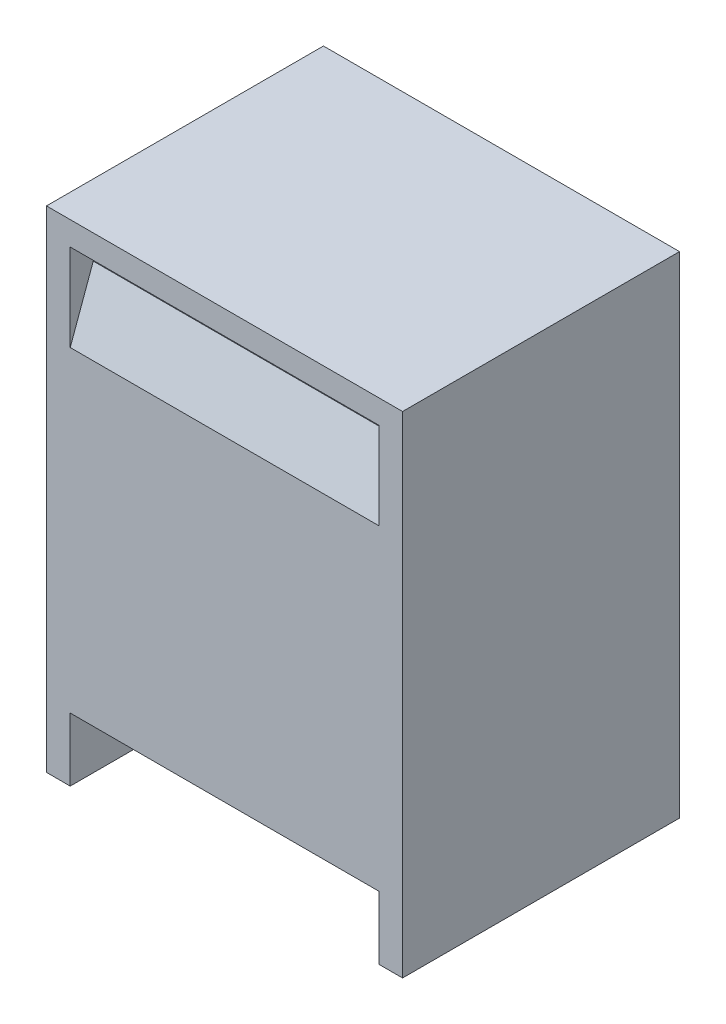
SolidWorks part; units mm, degrees
ref_plane "Alzado" through (0, 0, 0) normal (0, 0, 1) x (1, 0, 0)
ref_plane "Planta" through (0, 0, 0) normal (0, 1, 0) x (1, 0, 0)
ref_plane "Vista lateral" through (0, 0, 0) normal (1, 0, 0) x (0, 0, -1)
sketch "Croquis1" plane through (0, 0, 0) normal (0, 0, 1) x (1, 0, 0)
  line L1 (0, 0) -> (450, 0)
  line L2 (0, 0) -> (0, 620)
  line L3 (0, 620) -> (450, 620)
  line L4 (450, 0) -> (450, 620)
  dimension "D1" = 450
  dimension "D2" = 620
extrude "Saliente-Extruir1" add sketch "Croquis1" along normal blind 350
sketch "Croquis2" plane through (0, 0, 350) normal (0, 0, 1) x (1, 0, 0)
  line L0 (0, 0) -> (450, 0) construction
  line L1 (30, 0) -> (420, 0)
  line L2 (30, 0) -> (30, 80)
  line L3 (30, 80) -> (420, 80)
  line L4 (420, 0) -> (420, 80)
  line L5 (450, 0) -> (450, 620) construction
  line L6 (0, 620) -> (0, 0) construction
  dimension "D1" = 80
  dimension "D2" = 30
  dimension "D3" = 30
extrude "Cortar-Extruir1" cut sketch "Croquis2" against normal up to surface (350 mm away) up to face at (225, 310, 0)
sketch "Croquis3" plane through (0, 0, 350) normal (0, 0, 1) x (1, 0, 0)
  line L0 (450, 0) -> (450, 620) construction
  line L1 (30, 480) -> (420, 480)
  line L2 (30, 480) -> (30, 590)
  line L3 (30, 590) -> (420, 590)
  line L4 (420, 480) -> (420, 590)
  line L5 (0, 620) -> (0, 0) construction
  line L6 (450, 620) -> (0, 620) construction
  dimension "D1" = 30
  dimension "D2" = 30
  dimension "D3" = 30
  dimension "D4" = 110
extrude "Cortar-Extruir2" cut sketch "Croquis3" against normal up to surface (350 mm away) up to face at (225, 175, 0)
sketch "Croquis4" plane through (30, 0, 0) normal (1, 0, 0) x (0, 0, -1)
  line L0 (-350, 480) -> (-320.8824, 560)
  line L1 (-320.8824, 560) -> (-29.1176, 560)
  line L2 (-29.1176, 560) -> (0, 480)
  line L4 (-350, 0) -> (-350, 620) construction
  line L5 (0, 0) -> (0, 620) construction
  line L6 (-350, 480) -> (-350, 453.2735)
  line L7 (-350, 453.2735) -> (0, 453.2735)
  line L8 (0, 453.2735) -> (0, 480)
  dimension "D1" = 20
  dimension "D2" = 20
  dimension "D3" = 80
extrude "Saliente-Extruir2" add sketch "Croquis4" along normal up to surface (420 mm away) up to face at (450, 310, 175)
